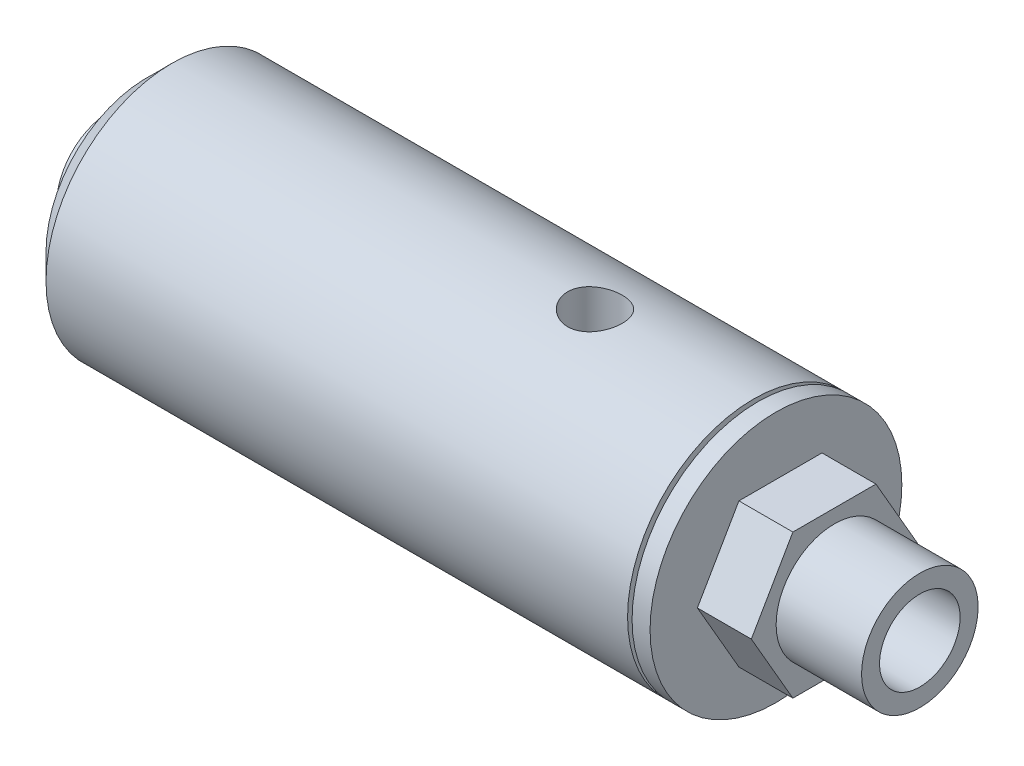
SolidWorks part; units mm, degrees
material "6061-T6 (SS)"
ref_plane "Front Plane" through (0, 0, 0) normal (0, 0, 1) x (1, 0, 0)
ref_plane "Top Plane" through (0, 0, 0) normal (0, 1, 0) x (1, 0, 0)
ref_plane "Right Plane" through (0, 0, 0) normal (1, 0, 0) x (0, 0, -1)
sketch "Sketch1" plane through (0, 0, 0) normal (0, 0, 1) x (1, 0, 0)
  line L0 (2.2451, 11.1125) -> (0, 8.8674)
  line L1 (0, 0) -> (55.5625, 0)
  line L2 (0, 4.7625) -> (0, 8.8674)
  line L3 (2.2451, 11.1125) -> (53.5781, 11.1125)
  line L4 (55.5625, 4.7625) -> (55.5625, 11.1125)
  line L5 (53.975, 11.1125) -> (55.5625, 11.1125)
  line L6 (60.7219, 5.1435) -> (68.2625, 5.1435)
  line L7 (53.5781, 11.1125) -> (53.5781, 10.0049)
  line L8 (53.5781, 10.0049) -> (53.975, 10.0049)
  line L9 (53.975, 11.1125) -> (53.975, 10.0049)
  line L10 (0, 0) -> (-3.175, 0)
  line L12 (0, 4.7625) -> (-3.175, 4.7625)
  line L13 (-3.175, 0) -> (-3.175, 4.7625)
  line L14 (55.5625, 0) -> (68.2625, 0)
  line L16 (55.5625, 4.7625) -> (55.9594, 4.7625)
  line L17 (68.2625, 0) -> (68.2625, 5.1435)
  line L19 (55.9594, 4.7625) -> (55.9594, 8.7454)
  line L20 (55.9594, 8.7454) -> (60.7219, 8.7454)
  line L21 (60.7219, 5.1435) -> (60.7219, 8.7454)
  dimension "D1" = 11.1125
  dimension "D2" = 1.5875
  dimension "D3" = 3.175
  dimension "D4" = 135
  dimension "D5" = 0.3969
  dimension "D6" = 55.5625
  dimension "D7" = 4.7625
  dimension "D8" = 3.175
  dimension "D9" = 12.7
  dimension "D10" = 5.1435
  dimension "D11" = 4.7625
  dimension "D12" = 0.3969
  dimension "D13" = 4.7625
revolve "Revolve1" add sketch "Sketch1" angle 360 about L1
sketch "Sketch2" plane through (60.7219, 0, 0) normal (1, 0, 0) x (0, 0, -1)
  line L0 (-3.6662, 6.35) -> (3.6662, 6.35)
  line L1 (3.6662, 6.35) -> (7.3323, 0)
  line L2 (7.3323, 0) -> (3.6662, -6.35)
  line L3 (3.6662, -6.35) -> (-3.6662, -6.35)
  line L4 (-3.6662, -6.35) -> (-7.3323, 0)
  line L5 (-7.3323, 0) -> (-3.6662, 6.35)
  line L6 (-3.6662, 6.35) -> (3.6662, -6.35) construction
  line L7 (3.6662, 6.35) -> (-3.6662, -6.35) construction
  circle A1 centre (0, 0) radius 8.7454 construction
  circle A2 centre (0, 0) radius 8.7454
  dimension "D1" = 120
  dimension "D2" = 12.7
extrude "Cut-Extrude1" cut sketch "Sketch2" against normal blind 5.0165
ref_plane "Plane1" through (0, 11.1125, 0) normal (0, 1, 0) x (1, 0, 0)
sketch "Sketch3" plane through (0, 11.1125, 0) normal (0, 1, 0) x (1, 0, 0)
  circle A0 centre (39.5903, 0) radius 2.413
  dimension "D1" = 4.826
extrude "Cut-Extrude2" cut sketch "Sketch3" against normal blind 11.557
sketch "Sketch4" plane through (68.2625, 0, 0) normal (1, 0, 0) x (0, 0, -1)
  circle A2 centre (0, 0) radius 3.556
  circle A3 centre (0, 0) radius 3.556
  dimension "D1" = 1.5875
extrude "Cut-Extrude3" cut sketch "Sketch4" against normal blind 62.865
